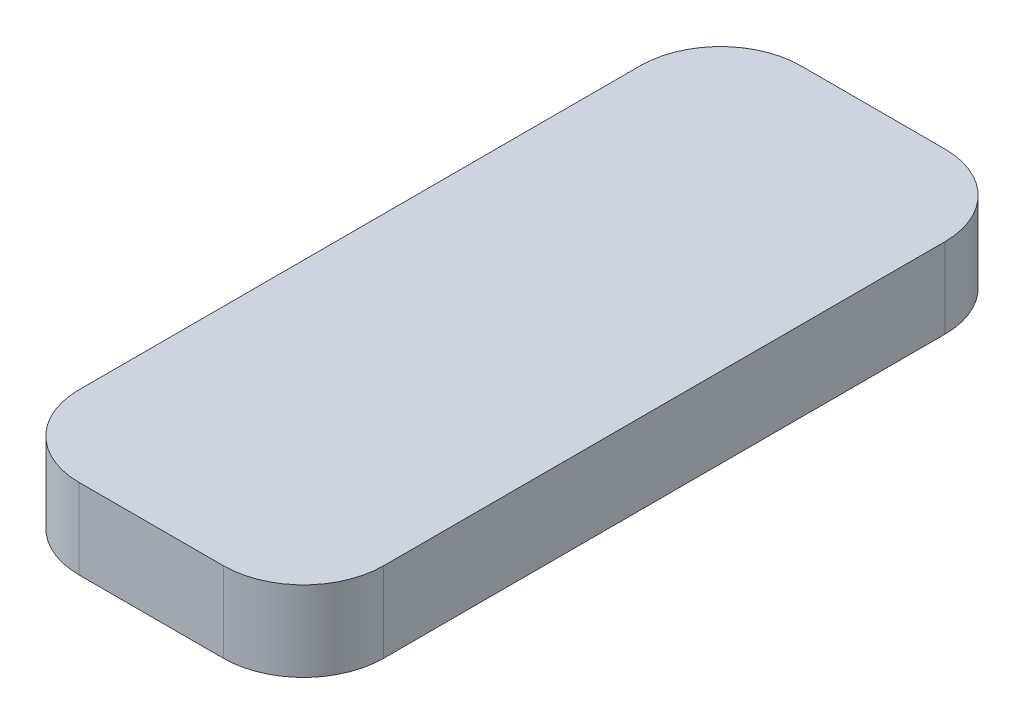
SolidWorks part; units mm, degrees
ref_plane "Front Plane" through (0, 0, 0) normal (0, 0, 1) x (1, 0, 0)
ref_plane "Top Plane" through (0, 0, 0) normal (0, 1, 0) x (1, 0, 0)
ref_plane "Right Plane" through (0, 0, 0) normal (1, 0, 0) x (0, 0, -1)
sketch "Sketch1" plane through (0, 0, 0) normal (0, 1, 0) x (1, 0, 0)
  circle A0 centre (0, 0) radius 38
extrude "Boss-Extrude1" add sketch "Sketch1" along normal blind 80
sketch "Sketch2" plane through (0, 0, 0) normal (0, -1, 0) x (1, 0, 0)
  circle A0 centre (0, 0) radius 29
extrude "Cut-Extrude1" cut sketch "Sketch2" against normal blind 75
sketch "Sketch3" plane through (0, 80, 0) normal (0, 1, 0) x (1, 0, 0)
  line L1 (18, -90) -> (-18, -90)
  line L2 (38, -70) -> (38, 70)
  line L3 (18, 90) -> (-18, 90)
  line L4 (-38, -70) -> (-38, 70)
  line L5 (38, -90) -> (-38, 90) construction
  line L6 (38, 90) -> (-38, -90) construction
  arc A1 (18, -90) -> (38, -70) centre (18, -70) ccw
  arc A2 (-18, -90) -> (-38, -70) centre (-18, -70) cw
  arc A3 (38, 70) -> (18, 90) centre (18, 70) ccw
  arc A4 (-18, 90) -> (-38, 70) centre (-18, 70) ccw
  point P0 (0, 0)
  dimension "D1" = 20
extrude "Boss-Extrude2" add sketch "Sketch3" along normal blind 20 contours L2 A3 L3 A4 L4 A2 L1 A1
sketch "Esboço1" plane through (38, 0, 0) normal (1, 0, 0) x (0, 0, -1)
  line L0 (38, 80) -> (38, 0)
  line L1 (38, 0) -> (-38, 0)
  line L2 (-38, 0) -> (-38, 80)
  line L3 (-38, 80) -> (38, 80)
extrude "Corte-extrusão1" cut sketch "Esboço1" against normal through all
sketch "Esboço2" plane through (0, 80, 0) normal (0, -1, 0) x (1, 0, 0)
  line L0 (17.5, -24.5) -> (17.5, 24.5)
  line L2 (20, -24.5) -> (20, 24.5)
  line L3 (-20, -24.5) -> (-20, 24.5)
  line L4 (-17.5, -24.5) -> (-17.5, 24.5)
  line L5 (20, -24.5) -> (17.5, -24.5)
  line L6 (20, 24.5) -> (17.5, 24.5)
  line L7 (-17.5, 24.5) -> (-20, 24.5)
  line L8 (-17.5, -24.5) -> (-20, -24.5)
  point P8 (20, 0)
  dimension "D1" = 40
  dimension "D2" = 2.5
  dimension "D3" = 2.5
extrude "Ressalto-extrusão1" add sketch "Esboço2" along normal blind 5.4
sketch "Esboço3" plane through (20, 0, 0) normal (1, 0, 0) x (0, 0, -1)
  line L0 (24.5, 74.6) -> (24.5, 80) construction
  line L1 (-70, 80) -> (70, 80) construction
  circle A0 centre (22, 77.3) radius 1.35
  circle A1 centre (0, 77.3) radius 1.35
  circle A2 centre (-22, 77.3) radius 1.35
  dimension "D1" = 2.5
  dimension "D2" = 22
  dimension "D3" = 22
  dimension "D4" = 2.7
  dimension "D5" = 2.7
  dimension "D6" = 2.7
  dimension "D7" = 2.7
  dimension "D8" = 2.7
  dimension "D9" = 2.7
extrude "Corte-extrusão2" cut sketch "Esboço3" against normal through all
fillet "Filete1" radius 2 4 edges at (-18.75, 74.6, -24.5) (-18.75, 74.6, 24.5) (18.75, 74.6, 24.5) (18.75, 74.6, -24.5)
